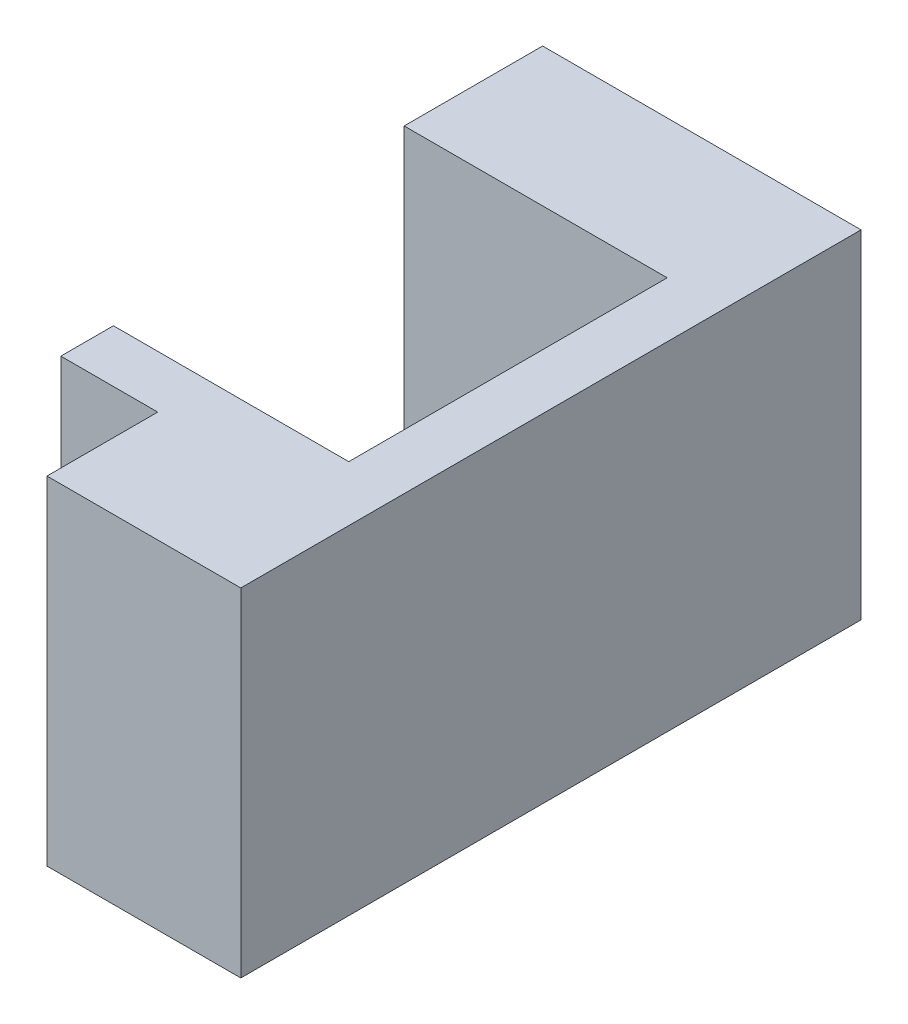
SolidWorks part; units mm, degrees
ref_plane "Front Plane" through (0, 0, 0) normal (0, 0, 1) x (1, 0, 0)
ref_plane "Top Plane" through (0, 0, 0) normal (0, 1, 0) x (1, 0, 0)
ref_plane "Right Plane" through (0, 0, 0) normal (1, 0, 0) x (0, 0, -1)
sketch "Sketch1" plane through (0, 0, 0) normal (0, 1, 0) x (1, 0, 0)
  line L0 (0, 0) -> (9.5, 0)
  line L1 (9.5, 0) -> (9.5, -11.5)
  line L2 (9.5, -11.5) -> (1, -11.5)
  line L3 (1, -11.5) -> (1, -13.4)
  line L4 (1, -13.4) -> (4.5, -13.4)
  line L6 (4.5, -17.4) -> (4.5, -13.4)
  line L8 (11.5, -17.4) -> (11.5, 5)
  line L9 (11.5, 5) -> (0, 5)
  line L10 (0, 5) -> (0, 0)
  line L11 (4.5, -17.4) -> (11.5, -17.4)
  point P8 (9.5, -5.75)
  point P14 (5.25, -11.5)
  dimension "D1" = 11.5
  dimension "D2" = 7
  dimension "D3" = 10.5
  dimension "D4" = 1.9
  dimension "D5" = 5
  dimension "D6" = 4
  dimension "D7" = 9.5
  dimension "D8" = 11.5
extrude "Boss-Extrude1" add sketch "Sketch1" along normal blind 12.2
